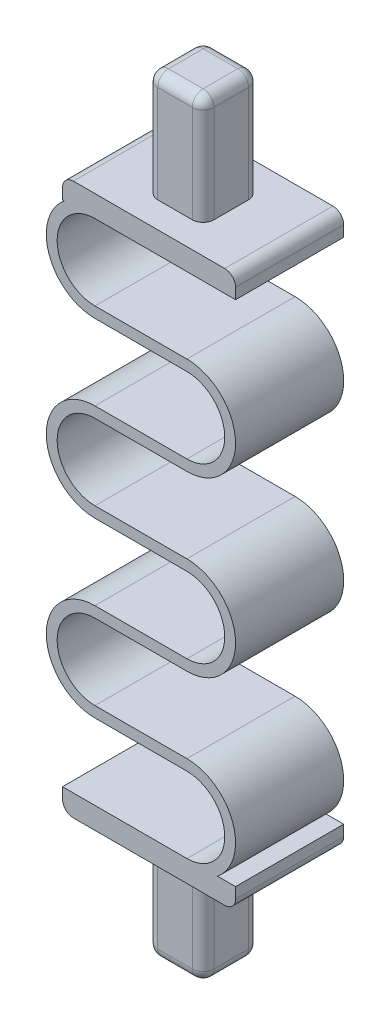
SolidWorks part; units mm, degrees
ref_plane "Front Plane" through (0, 0, 0) normal (0, 0, 1) x (1, 0, 0)
ref_plane "Top Plane" through (0, 0, 0) normal (0, 1, 0) x (1, 0, 0)
ref_plane "Right Plane" through (0, 0, 0) normal (1, 0, 0) x (0, 0, -1)
sketch "Sketch2" plane through (0, 0, 0) normal (0, 0, 1) x (1, 0, 0)
  line L1 (-4, -16.138) -> (4, -16.138)
  line L2 (-4, -16.138) -> (-4, -17.138)
  line L3 (-4, -17.138) -> (4, -17.138)
  line L4 (4, -16.138) -> (4, -17.138)
  line L5 (-4, 8.362) -> (4, 8.362)
  line L6 (-4, 8.362) -> (-4, 7.362)
  line L7 (-4, 7.362) -> (4, 7.362)
  line L8 (4, 8.362) -> (4, 7.362)
  line L28 (-4, 7.362) -> (6, 7.362)
  line L32 (1.75, -8.638) -> (-2.5, -8.638)
  line L33 (-4, 7.362) -> (6, 7.362)
  line L35 (-2.5, 3.862) -> (1.75, 3.862)
  line L37 (1.75, 3.862) -> (-2.5, 3.862)
  line L39 (1.75, -0.638) -> (-2.5, -0.638)
  line L41 (-2.5, -0.638) -> (1.75, -0.638)
  line L43 (-2.5, -4.138) -> (1.75, -4.138)
  line L45 (1.75, -4.138) -> (-2.5, -4.138)
  line L53 (-2.5, -12.138) -> (1.75, -12.138)
  line L54 (-2.5, 3.362) -> (1.75, 3.362)
  line L55 (1.75, -0.138) -> (-2.5, -0.138)
  line L56 (-2.5, -4.638) -> (1.75, -4.638)
  line L57 (1.75, -8.138) -> (-2.5, -8.138)
  line L58 (-2.5, -12.638) -> (1.75, -12.638)
  arc A7 (-2.5, 7.362) -> (-2.5, 3.862) centre (-2.5, 5.612) ccw
  arc A9 (-2.5, -0.638) -> (-2.5, -4.138) centre (-2.5, -2.388) ccw
  arc A12 (1.75, -0.638) -> (1.75, 3.862) centre (1.75, 1.612) ccw
  arc A13 (1.75, -8.638) -> (1.75, -4.138) centre (1.75, -6.388) ccw
  arc A14 (-2.5, -8.638) -> (-2.5, -12.138) centre (-2.5, -10.388) ccw
  arc A15 (1.75, -16.638) -> (1.75, -12.138) centre (1.75, -14.388) ccw
  arc A16 (-2.5, 7.862) -> (-2.5, 3.362) centre (-2.5, 5.612) ccw
  arc A17 (1.75, -0.138) -> (1.75, 3.362) centre (1.75, 1.612) ccw
  arc A18 (-2.5, -0.138) -> (-2.5, -4.638) centre (-2.5, -2.388) ccw
  arc A19 (1.75, -8.138) -> (1.75, -4.638) centre (1.75, -6.388) ccw
  arc A20 (-2.5, -8.138) -> (-2.5, -12.638) centre (-2.5, -10.388) ccw
  arc A21 (1.75, -16.138) -> (1.75, -12.638) centre (1.75, -14.388) ccw
  point P8 (0, -16.138)
  point P10 (0, 7.362)
  dimension "D4" = 3.5
  dimension "D3" = 0.5
  dimension "D7" = 3.5
  dimension "4" = 4.5
  dimension "D1" = 8
  dimension "D2" = 1
extrude "Boss-Extrude1" add sketch "Sketch2" along normal blind 5
sketch "Sketch3" plane through (0, 8.362, 0) normal (0, 1, 0) x (1, 0, 0)
  line L0 (0, 0) -> (0, -5) construction
  line L1 (-1.3, -3.8) -> (1.3, -3.8)
  line L2 (-1.3, -3.8) -> (-1.3, -1.2)
  line L3 (-1.3, -1.2) -> (1.3, -1.2)
  line L4 (1.3, -3.8) -> (1.3, -1.2)
  line L5 (-1.3, -3.8) -> (1.3, -1.2) construction
  line L6 (-1.3, -1.2) -> (1.3, -3.8) construction
  line L7 (-4, 0) -> (4, 0) construction
  line L8 (-4, -5) -> (4, -5) construction
  point P0 (0, -2.5)
  point P12 (0, -2.5)
  dimension "D1" = 2.6
  dimension "D2" = 2.6
extrude "Boss-Extrude2" add sketch "Sketch3" along normal blind 5
sketch "Sketch4" plane through (0, -17.138, 0) normal (0, -1, 0) x (1, 0, 0)
  line L0 (0, 5) -> (0, 0) construction
  line L1 (-4, 5) -> (4, 5) construction
  line L3 (1.3, 1.2) -> (-1.3, 1.2)
  line L4 (1.3, 1.2) -> (1.3, 3.8)
  line L5 (1.3, 3.8) -> (-1.3, 3.8)
  line L6 (-1.3, 1.2) -> (-1.3, 3.8)
  line L7 (1.3, 1.2) -> (-1.3, 3.8) construction
  line L8 (1.3, 3.8) -> (-1.3, 1.2) construction
  point P5 (0, 2.5)
  dimension "D1" = 2.6
  dimension "D2" = 2.6
extrude "Boss-Extrude3" add sketch "Sketch4" along normal blind 5
fillet "Fillet1" radius 0.5 20 edges at (0, 13.362, 3.8) (-1.3, 13.362, 2.5) (0, 13.362, 1.2) (1.3, 13.362, 2.5) (0, -22.138, 3.8) (1.3, -22.138, 2.5) (0, -22.138, 1.2) (-1.3, -22.138, 2.5) (4, -17.138, 2.5) (-4, -17.138, 2.5) (4, 8.362, 2.5) (-4, 8.362, 2.5) (-1.3, 10.862, 3.8) (-1.3, 10.862, 1.2) (1.3, 10.862, 3.8) (1.3, 10.862, 1.2) (1.3, -19.638, 1.2) (-1.3, -19.638, 1.2) (-1.3, -19.638, 3.8) (1.3, -19.638, 3.8)
